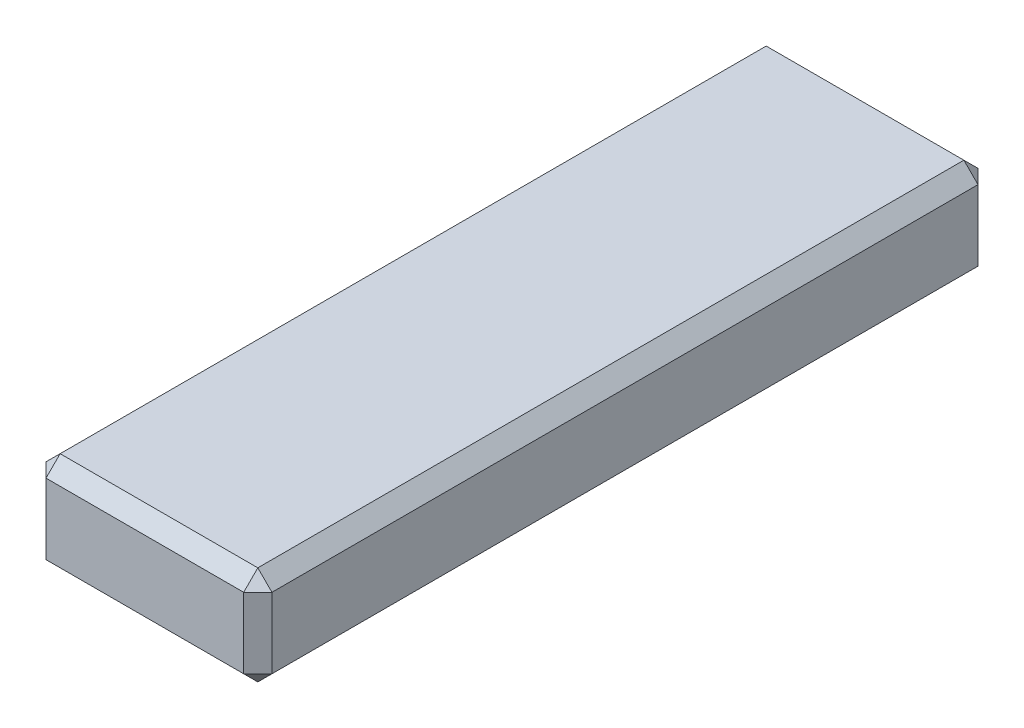
SolidWorks part; units mm, degrees
ref_plane "Front Plane" through (0, 0, 0) normal (0, 0, 1) x (1, 0, 0)
ref_plane "Top Plane" through (0, 0, 0) normal (0, 1, 0) x (1, 0, 0)
ref_plane "Right Plane" through (0, 0, 0) normal (1, 0, 0) x (0, 0, -1)
sketch "Sketch1" plane through (0, 0, 0) normal (0, 0, 1) x (1, 0, 0)
  line L1 (-4, 1.75) -> (4, 1.75)
  line L2 (-4, 1.75) -> (-4, -1.75)
  line L3 (-4, -1.75) -> (4, -1.75)
  line L4 (4, 1.75) -> (4, -1.75)
  line L5 (0, -1.75) -> (0, 1.75) construction
  line L6 (-4, 0) -> (4, 0) construction
  point P0 (0, 0)
  dimension "D1" = 3.5
  dimension "D2" = 8
extrude "Boss-Extrude1" add sketch "Sketch1" along normal mid plane 10
sketch "Sketch2" plane through (0, 0, -5) normal (0, 0, -1) x (-1, 0, 0)
  line L1 (-4, 1.75) -> (4, 1.75)
  line L2 (-4, 1.75) -> (-4, -1.75)
  line L3 (-4, -1.75) -> (4, -1.75)
  line L4 (4, 1.75) -> (4, -1.75)
  line L5 (0, -1.75) -> (0, 1.75) construction
  line L6 (-4, 0) -> (4, 0) construction
  point P0 (0, 0)
  dimension "D1" = 3.5
  dimension "D2" = 8
extrude "Boss-Extrude2" add sketch "Sketch2" along normal blind 8
mirror "Mirror1" about plane through (0, 0, 0) normal (0, 0, 1) of "Boss-Extrude2"
chamfer "Chamfer1" distance 0.5 angle 45 12 edges at (-4, 1.75, 0) (4, 0, 13) (0, 1.75, 13) (0, -1.75, 13) (-4, 0, 13) (-4, 0, -13) (0, 1.75, -13) (4, 1.75, 0) (4, 0, -13) (-4, -1.75, 0) (4, -1.75, 0) (0, -1.75, -13)
